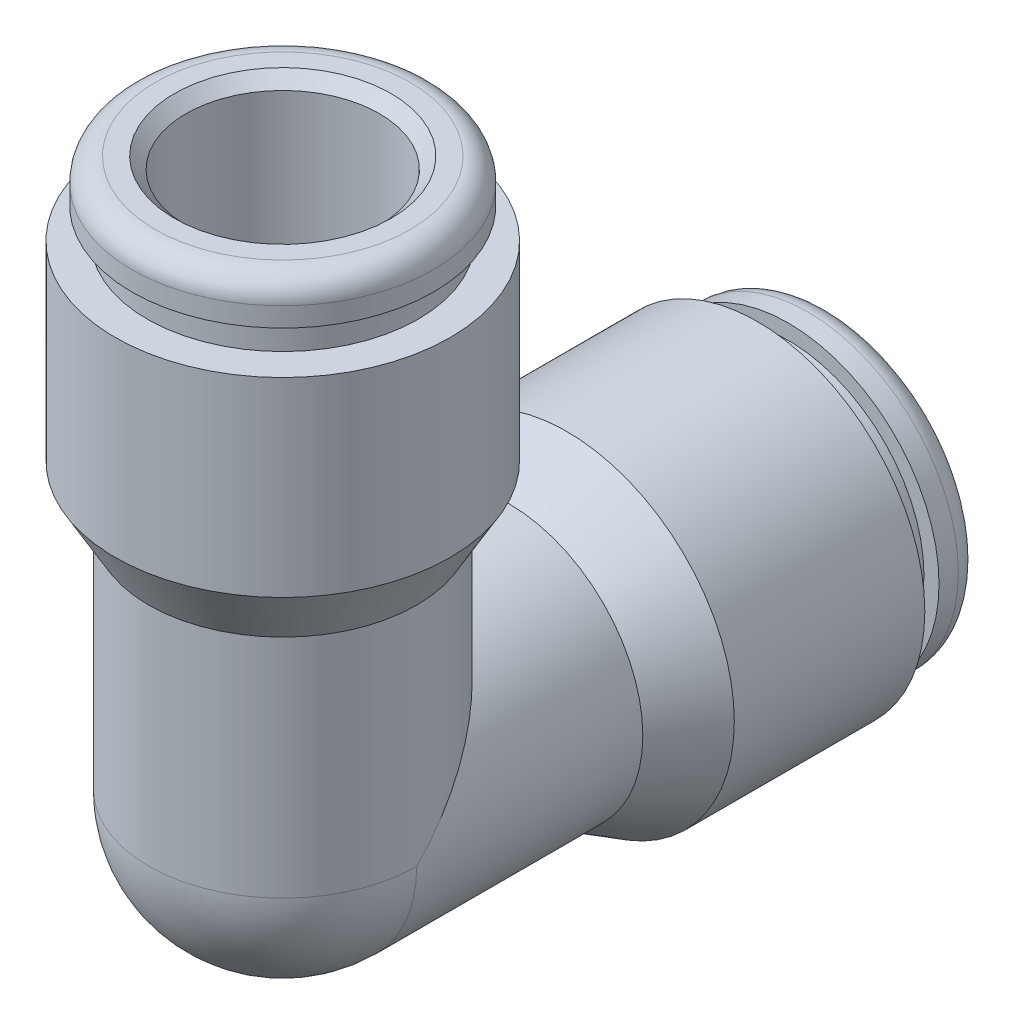
SolidWorks part; units mm, degrees
ref_plane "Front Plane" through (0, 0, 0) normal (0, 0, 1) x (1, 0, 0)
ref_plane "Top Plane" through (0, 0, 0) normal (0, 1, 0) x (1, 0, 0)
ref_plane "Right Plane" through (0, 0, 0) normal (1, 0, 0) x (0, 0, -1)
sketch "Sketch1" plane through (0, 0, 0) normal (1, 0, 0) x (0, 0, -1)
  line L0 (16.603, 4.95) -> (17.238, 4.95)
  line L1 (9.3303, 5.5) -> (15.587, 5.5)
  line L2 (0, 4.4) -> (0, 2.413)
  line L3 (3.4991, 3.175) -> (17.619, 3.175)
  line L4 (18, 4.188) -> (18, 3.556)
  line L5 (0, 0) -> (0, 18) construction
  line L6 (15.587, 5.5) -> (15.587, 4.455)
  line L7 (15.587, 4.455) -> (16.603, 4.455)
  line L8 (16.603, 4.95) -> (16.603, 4.455)
  line L9 (-5.5, 18) -> (5.5, 18) construction
  line L10 (0, 0) -> (18, 0) construction
  line L11 (3.4991, 3.175) -> (3.4991, 2.413)
  line L12 (17.619, 3.175) -> (18, 3.556)
  line L13 (0, 0) -> (0, 2.413) construction
  line L14 (0, 4.4) -> (7.425, 4.4)
  line L15 (7.425, 4.4) -> (9.3303, 5.5)
  line L16 (3.4991, 2.413) -> (0, 2.413)
  arc A0 (17.238, 4.95) -> (18, 4.188) centre (17.238, 4.188) cw
  point P1 (18, 3.175)
  point P20 (18, 4.95)
  dimension "D4" = 0.762
  dimension "tube od" = 6.35
  dimension "D1" = 1.397
  dimension "D2" = 1.016
  dimension "D3" = 8.91
  dimension "D6" = 9.9
  dimension "D9" = 30
  dimension "D10" = 8.8
  dimension "D5" = 10.575
  dimension "D8" = 11
  dimension "D11" = 0.762
revolve "Revolve1" add sketch "Sketch1" angle 360 about L10
ref_axis "Axis1" through (-15.8019, 0, 0) along (1, 0, 0)
pattern_circular "CirPattern1" count 2 over 90 about axis through (-15.8019, 0, 0) along (1, 0, 0) of bodies 118 123
sketch "Sketch2" plane through (0, 0, 0) normal (0, 0, 1) x (1, 0, 0)
  line L0 (-4.4, 0) -> (-2.413, 0)
  line L1 (-4.4, 0) -> (4.4, 0) construction
  line L2 (2.413, 0) -> (4.4, 0)
  arc A0 (-4.4, 0) -> (4.4, 0) centre (0, 0) ccw
  arc A2 (-2.413, 0) -> (2.413, 0) centre (0, 0) ccw
  circle A4 centre (0, 0) radius 2.413 construction
  circle A5 centre (0, 0) radius 4.4 construction
revolve "Revolve2" add sketch "Sketch2" angle 90 about L1
combine bodies "Combine1" operation type add bodies to combine 122 124
sketch "Sketch3" plane through (0, 0, 0) normal (1, 0, 0) x (0, 0, -1)
  line L0 (18, 3.556) -> (17.619, 3.175)
  line L1 (17.619, 3.175) -> (3.4991, 3.175)
  line L2 (3.4991, 3.175) -> (3.4991, 2.413)
  line L3 (3.4991, 2.413) -> (0, 2.413)
  line L4 (0, 2.413) -> (0, 0)
  line L5 (0, 0) -> (18, 0)
  line L6 (18, 0) -> (18, 3.556)
revolve "Cut-Revolve1" cut sketch "Sketch3" angle 360 about L5
pattern_circular "CirPattern2" count 2 over 90 about axis through (-15.8019, 0, 0) along (1, 0, 0) of "Cut-Revolve1"
equation "\"D3@Sketch1\" = \"D6@Sketch1\"*.9"
equation "\"D6@Sketch1\" = \"G@Sketch1\"*.9"
equation "\"D10@Sketch1\" = \"G@Sketch1\"*.8"
equation "\"D5@Sketch1\" = \"L@Sketch1\"*.45"
equation "\"D8@Sketch1\" = \"G@Sketch1\""
